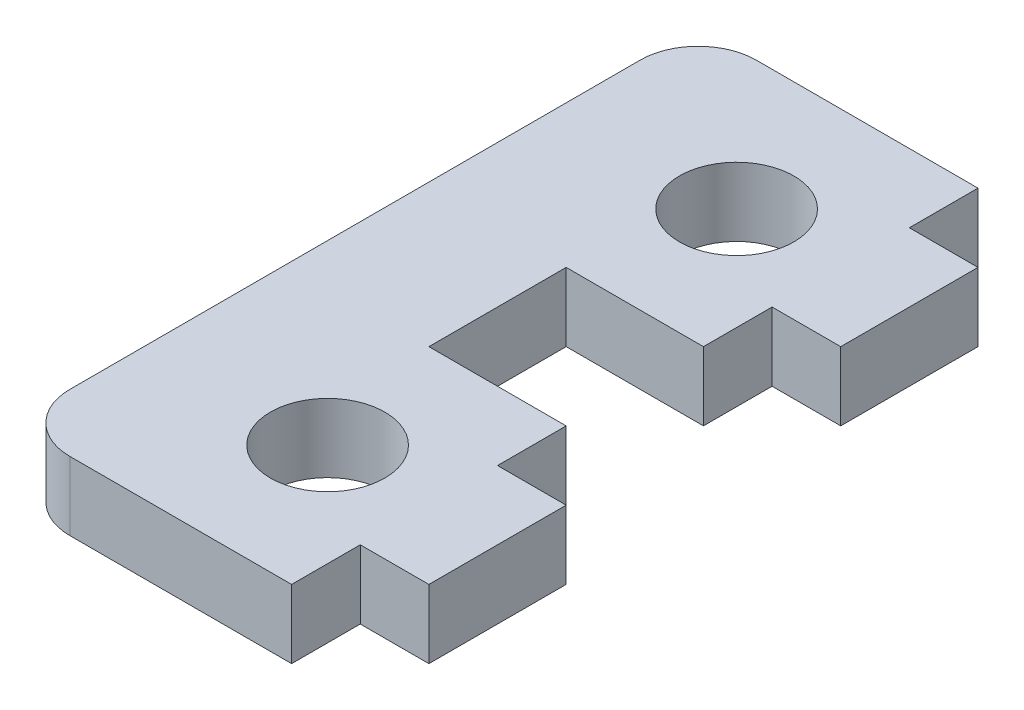
SolidWorks part; units mm, degrees
ref_plane "Front Plane" through (0, 0, 0) normal (0, 0, 1) x (1, 0, 0)
ref_plane "Top Plane" through (0, 0, 0) normal (0, 1, 0) x (1, 0, 0)
ref_plane "Right Plane" through (0, 0, 0) normal (1, 0, 0) x (0, 0, -1)
sketch "Sketch1" plane through (0, 0, 0) normal (0, 1, 0) x (1, 0, 0)
  line L0 (-21.1267, 18.92) -> (-21.1267, -30.92)
  line L1 (-16.0467, 24) -> (3.3322, 24)
  line L2 (3.3322, 24) -> (3.3322, 18)
  line L3 (3.3322, 18) -> (9.3322, 18)
  line L4 (9.3322, 18) -> (9.3322, 6)
  line L5 (9.3322, 6) -> (3.3322, 6)
  line L6 (3.3322, 6) -> (3.3322, 0)
  line L7 (3.3322, 0) -> (-8.6678, 0)
  line L8 (-8.6678, 0) -> (-8.6678, -12)
  line L9 (-8.6678, -12) -> (3.3322, -12)
  line L10 (3.3322, -12) -> (3.3322, -18)
  line L11 (3.3322, -18) -> (9.3322, -18)
  line L12 (9.3322, -18) -> (9.3322, -30)
  line L13 (3.3322, -36) -> (-16.0467, -36)
  line L14 (-5.6437, 11.8773) -> (-5.6437, -23.8773) construction
  line L15 (6.3322, 6) -> (6.3322, -18) construction
  line L17 (9.3322, -30) -> (3.3322, -30)
  line L18 (3.3322, -30) -> (3.3322, -36)
  circle A1 centre (-5.6437, 11.8773) radius 5
  circle A2 centre (-5.6437, -23.8773) radius 5
  arc A3 (-16.0467, -36) -> (-21.1267, -30.92) centre (-16.0467, -30.92) cw
  arc A4 (-21.1267, 18.92) -> (-16.0467, 24) centre (-16.0467, 18.92) cw
  point P0 (-5.6437, -6)
  point P11 (-8.6678, -6)
  point P15 (-21.1267, -6)
  dimension "D2" = 5.08
  dimension "D3" = 5.08
extrude "Boss-Extrude1" add sketch "Sketch1" along normal blind 6
